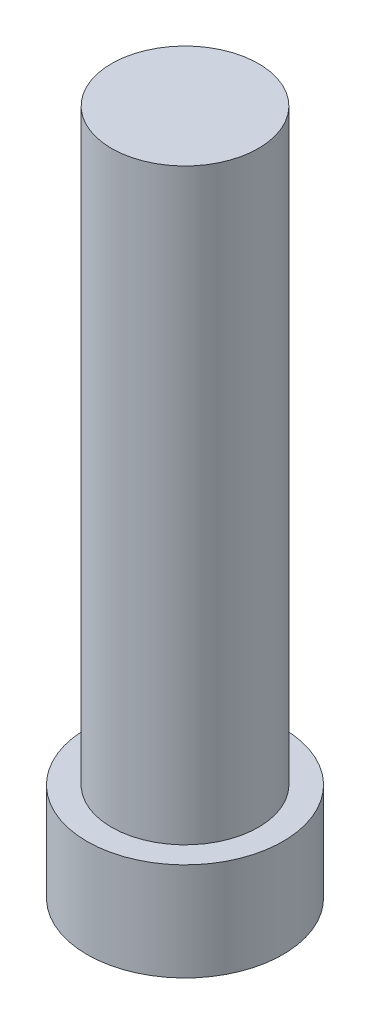
SolidWorks part; units mm, degrees
ref_plane "Front Plane" through (0, 0, 0) normal (0, 0, 1) x (1, 0, 0)
ref_plane "Top Plane" through (0, 0, 0) normal (0, 1, 0) x (1, 0, 0)
ref_plane "Right Plane" through (0, 0, 0) normal (1, 0, 0) x (0, 0, -1)
sketch "Sketch2" plane through (0, 0, 0) normal (0, 1, 0) x (1, 0, 0)
  circle A0 centre (0, 0) radius 10
  dimension "D1" = 20
extrude "Boss-Extrude1" add sketch "Sketch2" along normal blind 10
sketch "Sketch3" plane through (0, 10, 0) normal (0, 1, 0) x (1, 0, 0)
  circle A0 centre (0, 0) radius 7.5
  dimension "D1" = 15
extrude "Boss-Extrude2" add sketch "Sketch3" along normal blind 60
